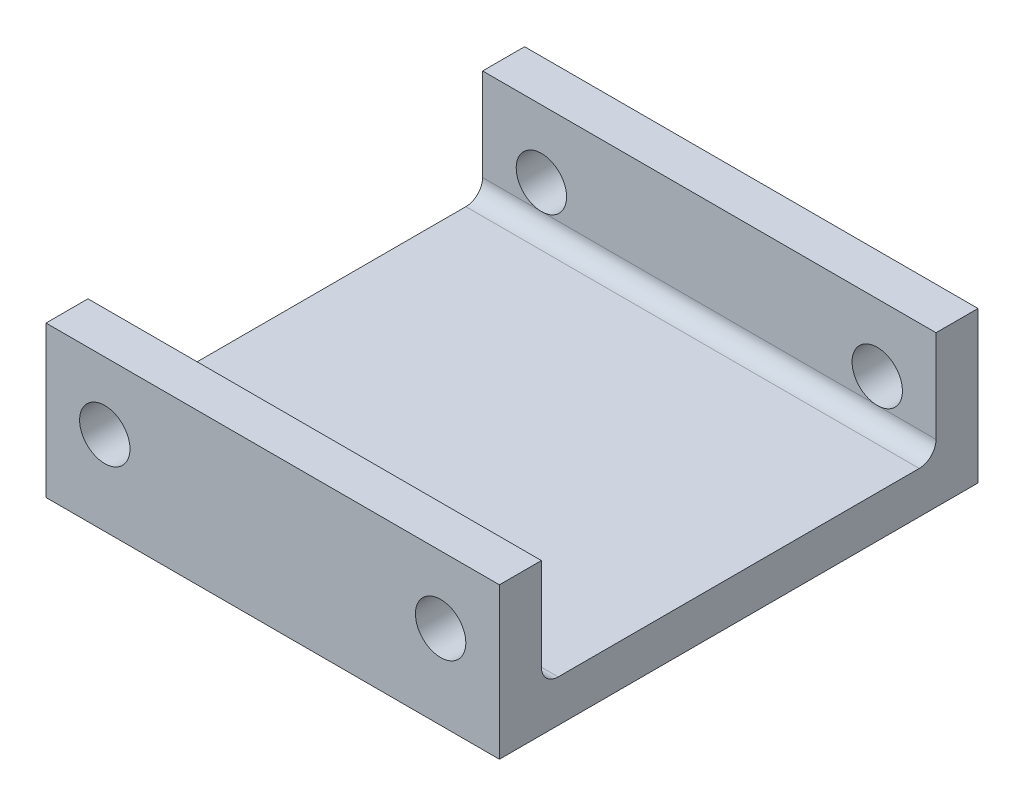
SolidWorks part; units mm, degrees
ref_plane "Plan de face" through (0, 0, 0) normal (0, 0, 1) x (1, 0, 0)
ref_plane "Plan de dessus" through (0, 0, 0) normal (0, 1, 0) x (1, 0, 0)
ref_plane "Plan de droite" through (0, 0, 0) normal (1, 0, 0) x (0, 0, -1)
sketch "Esquisse1" plane through (0, 0, 0) normal (0, 0, 1) x (1, 0, 0)
  line L0 (-27, 0) -> (27, 0)
  line L1 (-27, 0) -> (-27, -18)
  line L2 (27, 0) -> (27, -18)
  line L3 (-27, -18) -> (27, -18)
  circle A0 centre (-20, -8) radius 3
  circle A1 centre (20, -8) radius 3
  point P4 (0, 0)
  dimension "D4" = 6
  dimension "D1" = 54
  dimension "D2" = 18
  dimension "D3" = 18
  dimension "D5" = 7
  dimension "D6" = 8
  dimension "D7" = 2
extrude "Boss.-Extru.1" add sketch "Esquisse1" along normal blind 57
sketch "Esquisse3" plane through (-27, 0, 0) normal (-1, 0, 0) x (0, 0, 1)
  line L3 (52, 0) -> (5, 0)
  line L6 (5, -13) -> (52, -13)
  line L7 (52, -13) -> (52, 0)
  line L8 (5, 0) -> (5, -13)
  line L9 (7, -13) -> (50, -13)
  line L10 (52, -11) -> (52, 0)
  line L11 (5, 0) -> (5, -11)
  arc A0 (50, -13) -> (52, -11) centre (50, -11) ccw
  arc A1 (5, -11) -> (7, -13) centre (7, -11) ccw
  dimension "D2" = 2
  dimension "D1" = 5
extrude "Enlèv. mat.-Extru.1" cut sketch "Esquisse3" against normal blind 57
